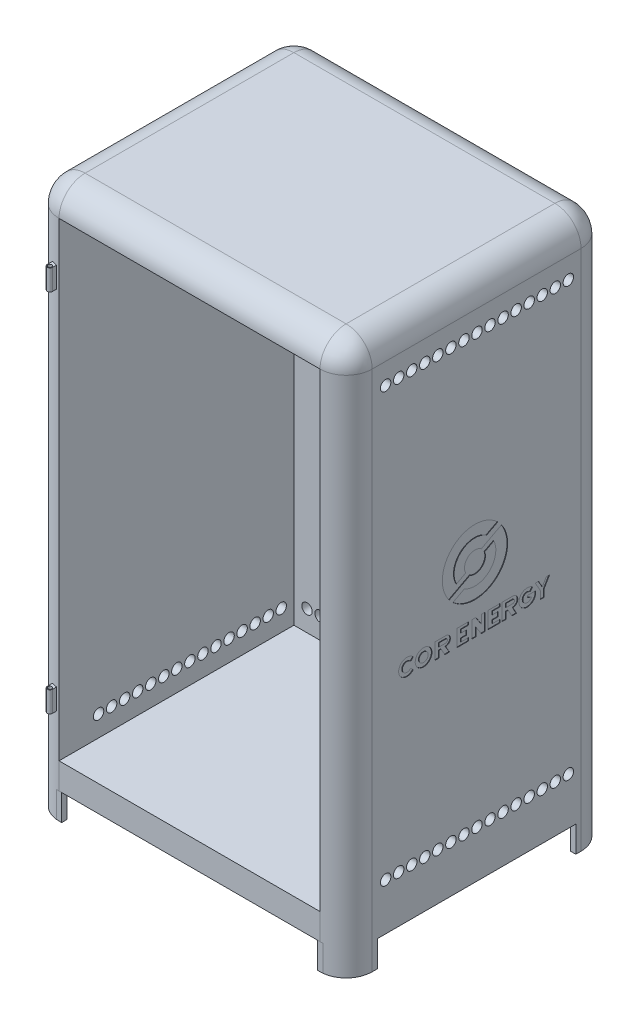
SolidWorks part; units mm, degrees
ref_plane "Front Plane" through (0, 0, 0) normal (0, 0, 1) x (1, 0, 0)
ref_plane "Top Plane" through (0, 0, 0) normal (0, 1, 0) x (1, 0, 0)
ref_plane "Right Plane" through (0, 0, 0) normal (1, 0, 0) x (0, 0, -1)
sketch "Sketch1" plane through (0, 0, 0) normal (0, 1, 0) x (1, 0, 0)
  line L1 (250, -250) -> (-250, -250)
  line L2 (300, -200) -> (300, 200)
  line L3 (250, 250) -> (-250, 250)
  line L4 (-300, -200) -> (-300, 200)
  line L5 (300, -250) -> (-300, 250) construction
  line L6 (300, 250) -> (-300, -250) construction
  arc A0 (300, -200) -> (250, -250) centre (250, -200) cw
  arc A1 (-300, -200) -> (-250, -250) centre (-250, -200) ccw
  arc A2 (250, 250) -> (300, 200) centre (250, 200) cw
  arc A3 (-250, 250) -> (-300, 200) centre (-250, 200) ccw
  point P0 (0, 0)
  dimension "D3" = 50
  dimension "D1" = 600
  dimension "D2" = 500
extrude "Boss-Extrude1" add sketch "Sketch1" along normal mid plane 1000
fillet "Fillet1" radius 50 8 edges at (0, 500, 250) (-285.3553, 500, 235.3553) (-300, 500, 0) (-285.3553, 500, -235.3553) (0, 500, -250) (285.3553, 500, -235.3553) (300, 500, 0) (285.3553, 500, 235.3553)
sketch "Sketch2" plane through (0, 0, 250) normal (0, 0, 1) x (1, 0, 0)
  line L1 (250, -450) -> (-250, -450)
  line L2 (250, -450) -> (250, 450)
  line L3 (250, 450) -> (-250, 450)
  line L4 (-250, -450) -> (-250, 450)
  line L5 (250, -450) -> (-250, 450) construction
  line L6 (250, 450) -> (-250, -450) construction
  point P0 (0, 0)
extrude "Cut-Extrude1" cut sketch "Sketch2" against normal blind 450
sketch "Sketch3" plane through (-250, 0, 0) normal (1, 0, 0) x (0, 0, -1)
  line L0 (-250, 450) -> (-250, -450) construction
  line L1 (-230, 370) -> (-257.5, 370)
  line L2 (-230, 370) -> (-230, 330)
  line L3 (-230, 330) -> (-257.5, 330)
  line L4 (-257.5, 370) -> (-257.5, 330)
  line L5 (-230, 370) -> (-257.5, 330) construction
  line L6 (-230, 330) -> (-257.5, 370) construction
  line L7 (200, 450) -> (-250, 450) construction
  point P0 (-243.75, 350)
  dimension "D1" = 100
  dimension "D2" = 27.5
  dimension "D3" = 40
  dimension "D4" = 20
extrude "Boss-Extrude2" add sketch "Sketch3" against normal blind 10 from offset 5 offset against normal yes
sketch "Sketch4" plane through (0, -500, 0) normal (0, -1, 0) x (1, 0, 0)
  line L0 (-300, 190) -> (-300, 200)
  line L1 (-300, -200) -> (-300, 200) construction
  line L4 (-255, 249.7494) -> (-245.0031, 250)
  line L6 (-290, 200) -> (-290, 190)
  line L7 (-290, 190) -> (-300, 190)
  line L8 (0, 404.1069) -> (0, -478.7655) construction
  line L9 (-352.0405, 0) -> (357.4973, 0) construction
  line L11 (300, 190) -> (300, 200)
  line L12 (290, 190) -> (300, 190)
  line L13 (290, 200) -> (290, 190)
  line L14 (245.0031, 240) -> (250, 240)
  line L15 (245.0031, 250) -> (245.0031, 240)
  line L16 (255, 249.7494) -> (245.0031, 250)
  line L29 (-250, 250) -> (250, 250) construction
  line L30 (-245.0031, 250) -> (-245.0031, 240)
  line L31 (-245.0031, 240) -> (-250, 240)
  line L32 (300, -190) -> (300, -200)
  line L33 (290, -190) -> (300, -190)
  line L34 (290, -200) -> (290, -190)
  line L35 (245.0031, -240) -> (250, -240)
  line L36 (245.0031, -250) -> (245.0031, -240)
  line L37 (255, -249.7494) -> (245.0031, -250)
  line L38 (-245.0031, -250) -> (-245.0031, -240)
  line L39 (-255, -249.7494) -> (-245.0031, -250)
  line L40 (-300, -190) -> (-300, -200)
  line L41 (-290, -190) -> (-300, -190)
  line L42 (-290, -200) -> (-290, -190)
  line L43 (-245.0031, -240) -> (-250, -240)
  arc A0 (-300, 200) -> (-255, 249.7494) centre (-250, 200) cw
  arc A1 (-250, 240) -> (-290, 200) centre (-250, 200) ccw
  arc A2 (300, 200) -> (255, 249.7494) centre (250, 200) ccw
  arc A3 (250, 240) -> (290, 200) centre (250, 200) cw
  arc A8 (250, -240) -> (290, -200) centre (250, -200) ccw
  arc A9 (300, -200) -> (255, -249.7494) centre (250, -200) cw
  arc A10 (-300, -200) -> (-255, -249.7494) centre (-250, -200) ccw
  arc A11 (-250, -240) -> (-290, -200) centre (-250, -200) cw
  dimension "D1" = 10
  dimension "D2" = 10
  dimension "D3" = 10
sketch "Sketch5" plane through (0, 370, 0) normal (0, 1, 0) x (1, 0, 0)
  line L1 (-255, -249.7494) -> (-255, -257.5) construction
  line L3 (-265, -257.5) -> (-255, -257.5) construction
  line L6 (-265, -257.5) -> (-265, -252.5)
  line L8 (-265, -252.5) -> (-255, -252.5)
  line L10 (-255, -252.5) -> (-255, -257.5)
  arc A2 (-255, -257.5) -> (-265, -257.5) centre (-260, -257.5) cw
extrude "Boss-Extrude4" add sketch "Sketch5" against normal up to surface (40 mm away) up to face at (-260.0131, 330, 253.1756)
sketch "Sketch6" plane through (0, 370, 0) normal (0, 1, 0) x (1, 0, 0)
  circle A0 centre (-260, -257.5) radius 3.75
  arc A1 (-265, -257.5) -> (-255, -257.5) centre (-260, -257.5) ccw construction
  dimension "D1" = 7.5
extrude "Cut-Extrude2" cut sketch "Sketch6" against normal up to surface (40 mm away) up to face at (-260.0131, 330, 254.4256)
mirror "Mirror1" about plane through (0, 0, 0) normal (0, 1, 0) of "Cut-Extrude2", "Boss-Extrude4", "Boss-Extrude2"
extrude "Boss-Extrude5" add sketch "Sketch4" along normal blind 50
sketch "Sketch7" plane through (300, 0, 0) normal (1, 0, 0) x (0, 0, -1)
  line L0 (-79.919, -62.7858) -> (-79.919, -93.4108)
  line L1 (-18.9571, -73.0337) -> (-18.9571, -81.7837)
  line L2 (44.6698, -93.4108) -> (44.6698, -87.5352)
  line L3 (67.6171, -93.4108) -> (60.4408, -80.5983)
  line L4 (14.1647, -93.4108) -> (16.4969, -93.4108) construction
  line L5 (-79.919, -62.7858) -> (-59.2696, -62.7858)
  line L6 (-37.7071, -61.4065) -> (-15.2071, -61.4065)
  line L7 (-8.9539, -61.4065) -> (-1.4539, -61.4065)
  line L8 (67.6171, -93.4108) -> (76.3671, -93.4108)
  line L9 (97.0706, -77.4087) -> (105.0111, -80.8927)
  line L10 (-29.8946, -81.7837) -> (-18.9571, -81.7837)
  line L11 (8.9969, -61.405) -> (16.4969, -61.405)
  line L12 (97.0706, -74.3057) -> (97.0706, -77.4087)
  line L13 (139.5417, -61.3356) -> (133.2917, -61.3356)
  line L14 (-1.4539, -77.4087) -> (-1.4539, -93.4108)
  line L15 (29.9823, -72.7917) -> (40.9198, -72.7917)
  line L16 (69.1908, -73.8541) -> (56.0414, -73.8541)
  line L17 (-29.8946, -67.0402) -> (-29.8946, -73.0337)
  line L18 (22.1698, -93.4108) -> (22.1698, -61.4065)
  line L19 (44.6698, -87.5352) -> (29.9823, -87.5352)
  line L20 (48.5414, -93.4108) -> (56.0414, -93.4108)
  line L21 (-68.0196, -80.5983) -> (-72.419, -80.5983)
  line L22 (-8.9539, -93.4108) -> (-8.9539, -61.4065)
  line L23 (22.1698, -61.4065) -> (44.6698, -61.4065)
  line L24 (112.7691, -74.3057) -> (97.0706, -74.3057)
  line L25 (18.9681, 64.7321) -> (40.473, 76.1384)
  line L26 (-59.2696, -80.5983) -> (-52.0933, -93.4108)
  line L27 (-15.2071, -61.4065) -> (-15.2071, -67.0402)
  line L28 (29.9823, -66.7982) -> (29.9823, -72.7917)
  line L29 (122.777, -79.5475) -> (112.2624, -61.3356)
  line L30 (133.2917, -61.3356) -> (125.902, -74.1348)
  line L31 (-45.4277, -14.6461) -> (-23.5105, -3.0211)
  line L32 (-60.8433, -93.4108) -> (-68.0196, -80.5983)
  line L33 (-37.7071, -93.4108) -> (-15.2071, -93.4108)
  line L34 (8.9969, -77.4087) -> (8.9969, -61.405)
  line L35 (112.2624, -61.3356) -> (118.5124, -61.3356)
  line L36 (15.2692, 39.0678) -> (32.9794, 48.4614)
  line L37 (-59.2696, -75.0983) -> (-72.419, -75.0983)
  line L38 (-15.2071, -67.0402) -> (-29.8946, -67.0402)
  line L39 (29.9823, -87.5352) -> (29.9823, -81.5417)
  line L40 (118.5124, -61.3356) -> (125.902, -74.1348)
  line L41 (9.0045, 47.2789) -> (47.6403, 67.7715)
  line L42 (105.0111, -80.8927) -> (97.0706, -77.4087) construction
  line L43 (-60.8433, -93.4108) -> (-52.0933, -93.4108)
  line L44 (-15.2071, -87.7772) -> (-29.8946, -87.7772)
  line L45 (56.0414, -80.5983) -> (56.0414, -93.4108)
  line L46 (122.777, -93.4108) -> (129.027, -93.4108)
  line L47 (-29.8946, -73.0337) -> (-18.9571, -73.0337)
  line L48 (16.4969, -61.405) -> (16.4969, -93.4108)
  line L49 (60.4408, -80.5983) -> (56.0414, -80.5983)
  line L50 (56.0414, -67.0416) -> (56.0414, -73.8541)
  line L51 (-126.4269, -83.0938) -> (-121.4612, -88.0595)
  line L52 (-29.8946, -87.7772) -> (-29.8946, -81.7837)
  line L53 (-8.9539, -93.4108) -> (-1.4539, -93.4108)
  line L54 (122.777, -93.4108) -> (122.777, -79.5475)
  line L55 (129.027, -79.5475) -> (139.5417, -61.3356)
  line L56 (8.9969, -93.4108) -> (16.4969, -93.4108)
  line L57 (29.9823, -81.5417) -> (40.9198, -81.5417)
  line L58 (48.5414, -61.3356) -> (69.1908, -61.3356)
  line L59 (-121.4612, -66.7578) -> (-126.4269, -71.7235)
  line L60 (-72.419, -68.2858) -> (-72.419, -75.0983)
  line L61 (8.9969, -93.4108) -> (-1.4539, -77.4087)
  line L62 (22.1698, -93.4108) -> (44.6698, -93.4108)
  line L63 (56.0414, -67.0416) -> (69.1908, -67.0416)
  line L64 (125.902, -93.4108) -> (122.777, -93.4108) construction
  line L65 (-37.7071, -93.4108) -> (-37.7071, -61.4065)
  line L66 (-15.2071, -93.4108) -> (-15.2071, -87.7772)
  line L67 (44.6698, -66.7982) -> (29.9823, -66.7982)
  line L68 (107.1759, -65.0008) -> (102.5464, -70.6852)
  line L69 (129.027, -93.4108) -> (129.027, -79.5475)
  line L70 (-72.419, -80.5983) -> (-72.419, -93.4108)
  line L71 (-72.419, -68.2858) -> (-59.2696, -68.2858)
  line L72 (44.6698, -61.4065) -> (44.6698, -66.7982)
  line L73 (48.5414, -61.3356) -> (48.5414, -93.4108)
  line L74 (-20.893, 22.0817) -> (-38.5615, 12.7103)
  line L75 (125.902, -93.4108) -> (125.902, -69.1382) construction
  line L76 (-79.919, -93.4108) -> (-72.419, -93.4108)
  line L77 (-1.4539, -61.4065) -> (8.9969, -77.4087)
  line L78 (40.9198, -72.7917) -> (40.9198, -81.5417)
  line L79 (69.1908, -80.5983) -> (76.3671, -93.4108)
  line L80 (-52.5786, -6.893) -> (-13.0866, 14.0538)
  line L81 (-8.9539, -93.4108) -> (-8.9539, -61.4065) construction
  arc A0 (-121.4612, -66.7578) -> (-121.4612, -88.0595) centre (-133.4039, -77.4087) ccw
  arc A1 (69.1908, -61.3356) -> (69.1908, -80.5983) centre (69.1908, -70.967) cw
  arc A2 (102.5464, -70.6852) -> (105.0111, -80.8927) centre (97.0706, -77.4087) ccw
  circle A3 centre (-101.6251, -77.4087) radius 16.0022
  arc A4 (9.0045, 47.2789) -> (-20.893, 22.0817) centre (-3.2245, 31.4532) ccw
  arc A5 (112.7691, -74.3057) -> (113.0728, -77.4087) centre (97.0706, -77.4087) cw
  arc A6 (18.9681, 64.7321) -> (-38.5615, 12.7103) centre (-3.2245, 31.4532) ccw
  arc A7 (40.473, 76.1384) -> (-52.5786, -6.893) centre (-3.2245, 31.4532) ccw
  arc A8 (-45.4277, -14.6461) -> (47.6403, 67.7715) centre (-3.2245, 31.4532) ccw
  arc A9 (-126.4269, -71.7235) -> (-126.4269, -83.0938) centre (-133.4039, -77.4087) ccw
  arc A10 (69.1908, -67.0416) -> (69.1908, -73.8541) centre (69.1908, -70.4479) cw
  circle A11 centre (-101.6251, -77.4087) radius 8.7649
  arc A12 (107.1759, -65.0008) -> (113.0728, -77.4087) centre (97.0706, -77.4087) ccw
  arc A13 (-13.0866, 14.0538) -> (15.2692, 39.0678) centre (-3.2245, 31.4532) ccw
  arc A14 (-23.5105, -3.0211) -> (32.9794, 48.4614) centre (-3.2245, 31.4532) ccw
  arc A15 (-59.2696, -62.7858) -> (-59.2696, -80.5983) centre (-59.2696, -71.6921) cw
  arc A16 (-59.2696, -68.2858) -> (-59.2696, -75.0983) centre (-59.2696, -71.6921) cw
  point P24 (-18.9571, -77.4087)
  point P30 (-37.7071, -77.4087)
  point P31 (33.3207, -77.4087)
  point P40 (40.9198, -77.1667)
  point P46 (22.1698, -77.4087)
  point P51 (61.5709, -77.4087)
  point P89 (14.1647, -93.4108)
  point P97 (61.5709, -70.967)
extrude "Cut-Extrude3" cut sketch "Sketch7" against normal blind 1
sketch "Sketch8" plane through (300, 0, 0) normal (1, 0, 0) x (0, 0, -1)
  line L0 (-185.104, 410) -> (170.278, 410) construction
  line L1 (200, 450) -> (-200, 450) construction
  line L2 (-200, 0) -> (200, 0) construction
  line L3 (-200, 450) -> (-200, -550) construction
  line L4 (200, 450) -> (200, -550) construction
  line L5 (-185.104, -410) -> (170.278, -410) construction
  circle A0 centre (-174.2978, 410) radius 10
  circle A1 centre (-149.2978, 410) radius 10
  circle A2 centre (-124.2978, 410) radius 10
  circle A3 centre (-99.2978, 410) radius 10
  circle A4 centre (-74.2978, 410) radius 10
  circle A5 centre (-49.2978, 410) radius 10
  circle A6 centre (-24.2978, 410) radius 10
  circle A7 centre (0.7022, 410) radius 10
  circle A8 centre (25.7022, 410) radius 10
  circle A9 centre (50.7022, 410) radius 10
  circle A10 centre (75.7022, 410) radius 10
  circle A11 centre (100.7022, 410) radius 10
  circle A12 centre (125.7022, 410) radius 10
  circle A13 centre (150.7022, 410) radius 10
  circle A14 centre (175.7022, 410) radius 10
  circle A15 centre (175.7022, -410) radius 10
  circle A16 centre (150.7022, -410) radius 10
  circle A17 centre (125.7022, -410) radius 10
  circle A18 centre (100.7022, -410) radius 10
  circle A19 centre (75.7022, -410) radius 10
  circle A20 centre (50.7022, -410) radius 10
  circle A21 centre (25.7022, -410) radius 10
  circle A22 centre (0.7022, -410) radius 10
  circle A23 centre (-24.2978, -410) radius 10
  circle A24 centre (-49.2978, -410) radius 10
  circle A25 centre (-74.2978, -410) radius 10
  circle A26 centre (-99.2978, -410) radius 10
  circle A27 centre (-124.2978, -410) radius 10
  circle A28 centre (-149.2978, -410) radius 10
  circle A29 centre (-174.2978, -410) radius 10
  dimension "D2" = 20
  dimension "D4" = 410
  dimension "D1" = 40
  dimension "D3" = 15
extrude "Cut-Extrude4" cut sketch "Sketch8" against normal through all
sketch "Sketch9" plane through (0, 0, -250) normal (0, 0, -1) x (-1, 0, 0)
  line L0 (-250, 410) -> (250, 410) construction
  line L1 (-250, 450) -> (-250, -500) construction
  line L2 (250, 450) -> (250, -500) construction
  line L6 (-250, 0) -> (250, 0) construction
  line L7 (-250, -410) -> (250, -410) construction
  line L8 (250, 450) -> (-250, 450) construction
  circle A0 centre (-225.056, 410) radius 10
  circle A1 centre (-200.056, 410) radius 10
  circle A2 centre (-175.056, 410) radius 10
  circle A3 centre (-150.056, 410) radius 10
  circle A4 centre (-125.056, 410) radius 10
  circle A5 centre (-100.056, 410) radius 10
  circle A6 centre (-75.056, 410) radius 10
  circle A7 centre (-50.056, 410) radius 10
  circle A8 centre (-25.056, 410) radius 10
  circle A9 centre (-0.056, 410) radius 10
  circle A10 centre (24.944, 410) radius 10
  circle A11 centre (49.944, 410) radius 10
  circle A12 centre (74.944, 410) radius 10
  circle A13 centre (99.944, 410) radius 10
  circle A14 centre (124.944, 410) radius 10
  circle A15 centre (149.944, 410) radius 10
  circle A16 centre (174.944, 410) radius 10
  circle A17 centre (199.944, 410) radius 10
  circle A18 centre (224.944, 410) radius 10
  circle A19 centre (224.944, -410) radius 10
  circle A20 centre (199.944, -410) radius 10
  circle A21 centre (174.944, -410) radius 10
  circle A22 centre (149.944, -410) radius 10
  circle A23 centre (124.944, -410) radius 10
  circle A24 centre (99.944, -410) radius 10
  circle A25 centre (74.944, -410) radius 10
  circle A26 centre (49.944, -410) radius 10
  circle A27 centre (24.944, -410) radius 10
  circle A28 centre (-0.056, -410) radius 10
  circle A29 centre (-25.056, -410) radius 10
  circle A30 centre (-50.056, -410) radius 10
  circle A31 centre (-75.056, -410) radius 10
  circle A32 centre (-100.056, -410) radius 10
  circle A33 centre (-125.056, -410) radius 10
  circle A34 centre (-150.056, -410) radius 10
  circle A35 centre (-175.056, -410) radius 10
  circle A36 centre (-200.056, -410) radius 10
  circle A37 centre (-225.056, -410) radius 10
  point P8 (0, 0)
  dimension "D1" = 20
  dimension "D3" = 410
  dimension "D4" = 40
  dimension "D2" = 19
extrude "Cut-Extrude5" cut sketch "Sketch9" against normal through all
